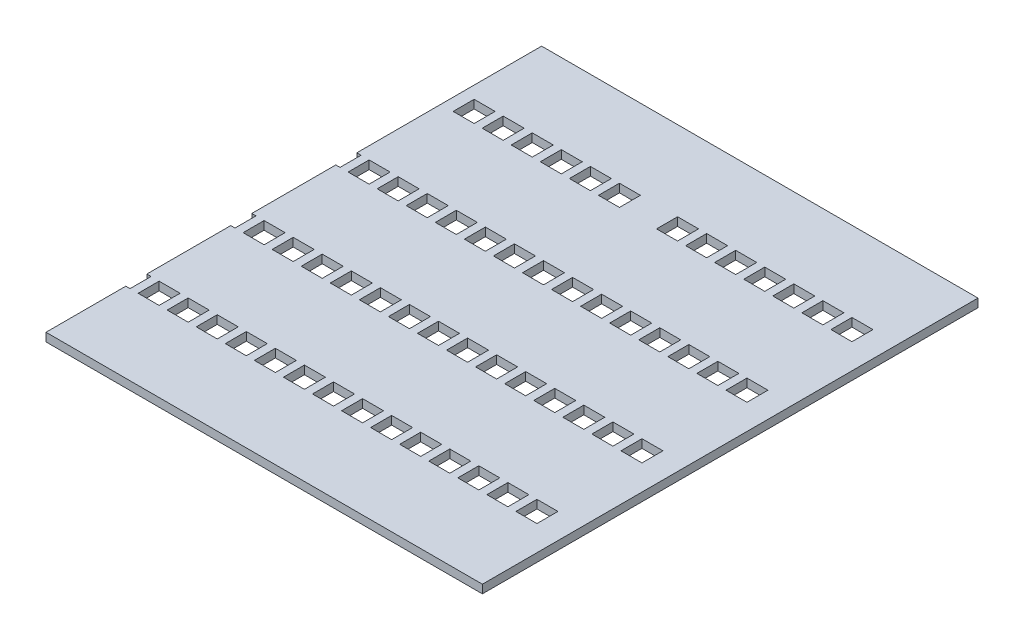
SolidWorks part; units mm, degrees
ref_plane "Front Plane" through (0, 0, 0) normal (0, 0, 1) x (1, 0, 0)
ref_plane "Top Plane" through (0, 0, 0) normal (0, 1, 0) x (1, 0, 0)
ref_plane "Right Plane" through (0, 0, 0) normal (1, 0, 0) x (0, 0, -1)
sketch "Sketch3" plane through (0, 0, 0) normal (0, 1, 0) x (1, 0, 0)
  line L0 (-9.3432, 44.989) -> (-9.3432, 39.989)
  line L1 (-60.7132, 63.989) -> (43.1868, 63.989)
  line L2 (-60.7132, 63.989) -> (-60.7132, -54.011)
  line L3 (-60.7132, -54.011) -> (43.1868, -54.011)
  line L4 (43.1868, 63.989) -> (43.1868, -54.011)
  line L9 (-16.2632, 44.989) -> (-11.2632, 39.989) construction
  line L10 (-16.2632, 39.989) -> (-11.2632, 44.989) construction
  line L11 (-9.3432, 44.989) -> (-4.3432, 44.989)
  line L12 (-4.3432, 44.989) -> (-4.3432, 39.989)
  line L13 (-9.3432, 39.989) -> (-4.3432, 39.989)
  line L14 (-9.3432, 44.989) -> (-4.3432, 39.989) construction
  line L15 (-9.3432, 39.989) -> (-4.3432, 44.989) construction
  line L16 (-2.4232, 44.989) -> (-2.4232, 39.989)
  line L17 (-2.4232, 44.989) -> (2.5768, 44.989)
  line L18 (2.5768, 44.989) -> (2.5768, 39.989)
  line L19 (-2.4232, 39.989) -> (2.5768, 39.989)
  line L20 (-2.4232, 44.989) -> (2.5768, 39.989) construction
  line L21 (-2.4232, 39.989) -> (2.5768, 44.989) construction
  line L22 (4.4968, 44.989) -> (4.4968, 39.989)
  line L23 (4.4968, 44.989) -> (9.4968, 44.989)
  line L24 (9.4968, 44.989) -> (9.4968, 39.989)
  line L25 (4.4968, 39.989) -> (9.4968, 39.989)
  line L26 (4.4968, 44.989) -> (9.4968, 39.989) construction
  line L27 (4.4968, 39.989) -> (9.4968, 44.989) construction
  line L28 (11.4168, 44.989) -> (11.4168, 39.989)
  line L29 (11.4168, 44.989) -> (16.4168, 44.989)
  line L30 (16.4168, 44.989) -> (16.4168, 39.989)
  line L31 (11.4168, 39.989) -> (16.4168, 39.989)
  line L32 (11.4168, 44.989) -> (16.4168, 39.989) construction
  line L33 (11.4168, 39.989) -> (16.4168, 44.989) construction
  line L34 (18.3368, 44.989) -> (18.3368, 39.989)
  line L35 (18.3368, 44.989) -> (23.3368, 44.989)
  line L36 (23.3368, 44.989) -> (23.3368, 39.989)
  line L37 (18.3368, 39.989) -> (23.3368, 39.989)
  line L38 (18.3368, 44.989) -> (23.3368, 39.989) construction
  line L39 (18.3368, 39.989) -> (23.3368, 44.989) construction
  line L40 (25.2568, 44.989) -> (25.2568, 39.989)
  line L41 (25.2568, 44.989) -> (30.2568, 44.989)
  line L42 (30.2568, 44.989) -> (30.2568, 39.989)
  line L43 (25.2568, 39.989) -> (30.2568, 39.989)
  line L46 (32.1768, 44.989) -> (32.1768, 39.989)
  line L47 (32.1768, 44.989) -> (37.1768, 44.989)
  line L48 (37.1768, 44.989) -> (37.1768, 39.989)
  line L49 (32.1768, 39.989) -> (37.1768, 39.989)
  line L52 (-16.2632, 44.989) -> (-9.3432, 44.989) construction
  line L53 (-23.1832, 44.989) -> (-23.1832, 39.989)
  line L54 (-23.1832, 44.989) -> (-18.1832, 44.989)
  line L55 (-18.1832, 44.989) -> (-18.1832, 39.989)
  line L56 (-23.1832, 39.989) -> (-18.1832, 39.989)
  line L57 (-23.1832, 44.989) -> (-18.1832, 39.989) construction
  line L58 (-23.1832, 39.989) -> (-18.1832, 44.989) construction
  line L59 (-30.1032, 44.989) -> (-30.1032, 39.989)
  line L60 (-30.1032, 44.989) -> (-25.1032, 44.989)
  line L61 (-25.1032, 44.989) -> (-25.1032, 39.989)
  line L62 (-30.1032, 39.989) -> (-25.1032, 39.989)
  line L63 (-30.1032, 44.989) -> (-25.1032, 39.989) construction
  line L64 (-30.1032, 39.989) -> (-25.1032, 44.989) construction
  line L65 (-37.0232, 44.989) -> (-37.0232, 39.989)
  line L66 (-37.0232, 44.989) -> (-32.0232, 44.989)
  line L67 (-32.0232, 44.989) -> (-32.0232, 39.989)
  line L68 (-37.0232, 39.989) -> (-32.0232, 39.989)
  line L69 (-37.0232, 44.989) -> (-32.0232, 39.989) construction
  line L70 (-37.0232, 39.989) -> (-32.0232, 44.989) construction
  line L71 (-43.9432, 44.989) -> (-43.9432, 39.989)
  line L72 (-43.9432, 44.989) -> (-38.9432, 44.989)
  line L73 (-38.9432, 44.989) -> (-38.9432, 39.989)
  line L74 (-43.9432, 39.989) -> (-38.9432, 39.989)
  line L75 (-43.9432, 44.989) -> (-38.9432, 39.989) construction
  line L76 (-43.9432, 39.989) -> (-38.9432, 44.989) construction
  line L77 (-50.8632, 44.989) -> (-50.8632, 39.989)
  line L78 (-50.8632, 44.989) -> (-45.8632, 44.989)
  line L79 (-45.8632, 44.989) -> (-45.8632, 39.989)
  line L80 (-50.8632, 39.989) -> (-45.8632, 39.989)
  line L81 (-50.8632, 44.989) -> (-45.8632, 39.989) construction
  line L82 (-50.8632, 39.989) -> (-45.8632, 44.989) construction
  line L96 (-57.7832, 44.989) -> (-57.7832, 39.989)
  line L97 (-57.7832, 39.989) -> (-52.7832, 39.989)
  line L98 (-52.7832, 44.989) -> (-52.7832, 39.989)
  line L99 (-57.7832, 44.989) -> (-52.7832, 44.989)
  line L100 (-57.7832, 39.989) -> (-52.7832, 44.989) construction
  line L101 (-57.7832, 44.989) -> (-52.7832, 39.989) construction
  line L102 (-50.8632, 44.989) -> (-50.8632, 39.989)
  line L103 (-50.8632, 39.989) -> (-45.8632, 39.989)
  line L104 (-45.8632, 44.989) -> (-45.8632, 39.989)
  line L105 (-50.8632, 44.989) -> (-45.8632, 44.989)
  line L106 (-50.8632, 39.989) -> (-45.8632, 44.989) construction
  line L107 (-50.8632, 44.989) -> (-45.8632, 39.989) construction
  line L108 (-43.9432, 44.989) -> (-43.9432, 39.989)
  line L109 (-43.9432, 39.989) -> (-38.9432, 39.989)
  line L110 (-38.9432, 44.989) -> (-38.9432, 39.989)
  line L111 (-43.9432, 44.989) -> (-38.9432, 44.989)
  line L112 (-43.9432, 39.989) -> (-38.9432, 44.989) construction
  line L113 (-43.9432, 44.989) -> (-38.9432, 39.989) construction
  line L114 (-37.0232, 44.989) -> (-37.0232, 39.989)
  line L115 (-37.0232, 39.989) -> (-32.0232, 39.989)
  line L116 (-32.0232, 44.989) -> (-32.0232, 39.989)
  line L117 (-37.0232, 44.989) -> (-32.0232, 44.989)
  line L118 (-37.0232, 39.989) -> (-32.0232, 44.989) construction
  line L119 (-37.0232, 44.989) -> (-32.0232, 39.989) construction
  line L120 (-30.1032, 44.989) -> (-30.1032, 39.989)
  line L121 (-30.1032, 39.989) -> (-25.1032, 39.989)
  line L122 (-25.1032, 44.989) -> (-25.1032, 39.989)
  line L123 (-30.1032, 44.989) -> (-25.1032, 44.989)
  line L124 (-30.1032, 39.989) -> (-25.1032, 44.989) construction
  line L125 (-30.1032, 44.989) -> (-25.1032, 39.989) construction
  line L126 (-23.1832, 44.989) -> (-23.1832, 39.989)
  line L127 (-23.1832, 39.989) -> (-18.1832, 39.989)
  line L128 (-18.1832, 44.989) -> (-18.1832, 39.989)
  line L129 (-23.1832, 44.989) -> (-18.1832, 44.989)
  line L130 (-23.1832, 39.989) -> (-18.1832, 44.989) construction
  line L131 (-23.1832, 44.989) -> (-18.1832, 39.989) construction
  line L136 (-16.2632, 39.989) -> (-11.2632, 44.989) construction
  line L137 (-16.2632, 44.989) -> (-11.2632, 39.989) construction
  line L138 (-9.3432, 44.989) -> (-9.3432, 39.989)
  line L139 (-9.3432, 39.989) -> (-4.3432, 39.989)
  line L140 (-4.3432, 44.989) -> (-4.3432, 39.989)
  line L141 (-9.3432, 44.989) -> (-4.3432, 44.989)
  line L142 (-9.3432, 39.989) -> (-4.3432, 44.989) construction
  line L143 (-9.3432, 44.989) -> (-4.3432, 39.989) construction
  line L144 (-2.4232, 44.989) -> (-2.4232, 39.989)
  line L145 (-2.4232, 39.989) -> (2.5768, 39.989)
  line L146 (2.5768, 44.989) -> (2.5768, 39.989)
  line L147 (-2.4232, 44.989) -> (2.5768, 44.989)
  line L148 (-2.4232, 39.989) -> (2.5768, 44.989) construction
  line L149 (-2.4232, 44.989) -> (2.5768, 39.989) construction
  line L150 (4.4968, 44.989) -> (4.4968, 39.989)
  line L151 (4.4968, 39.989) -> (9.4968, 39.989)
  line L152 (9.4968, 44.989) -> (9.4968, 39.989)
  line L153 (4.4968, 44.989) -> (9.4968, 44.989)
  line L154 (4.4968, 39.989) -> (9.4968, 44.989) construction
  line L155 (4.4968, 44.989) -> (9.4968, 39.989) construction
  line L156 (11.4168, 44.989) -> (11.4168, 39.989)
  line L157 (11.4168, 39.989) -> (16.4168, 39.989)
  line L158 (16.4168, 44.989) -> (16.4168, 39.989)
  line L159 (11.4168, 44.989) -> (16.4168, 44.989)
  line L160 (11.4168, 39.989) -> (16.4168, 44.989) construction
  line L161 (11.4168, 44.989) -> (16.4168, 39.989) construction
  line L162 (18.3368, 44.989) -> (18.3368, 39.989)
  line L163 (18.3368, 39.989) -> (23.3368, 39.989)
  line L164 (23.3368, 44.989) -> (23.3368, 39.989)
  line L165 (18.3368, 44.989) -> (23.3368, 44.989)
  line L166 (18.3368, 39.989) -> (23.3368, 44.989) construction
  line L167 (18.3368, 44.989) -> (23.3368, 39.989) construction
  line L168 (25.2568, 44.989) -> (25.2568, 39.989)
  line L169 (25.2568, 39.989) -> (30.2568, 39.989)
  line L170 (30.2568, 44.989) -> (30.2568, 39.989)
  line L171 (25.2568, 44.989) -> (30.2568, 44.989)
  line L172 (25.2568, 39.989) -> (30.2568, 44.989) construction
  line L173 (25.2568, 44.989) -> (30.2568, 39.989) construction
  line L174 (32.1768, 44.989) -> (32.1768, 39.989)
  line L175 (32.1768, 39.989) -> (37.1768, 39.989)
  line L176 (37.1768, 44.989) -> (37.1768, 39.989)
  line L177 (32.1768, 44.989) -> (37.1768, 44.989)
  line L178 (32.1768, 39.989) -> (37.1768, 44.989) construction
  line L179 (32.1768, 44.989) -> (37.1768, 39.989) construction
  line L180 (-57.7832, 19.989) -> (-57.7832, 14.989)
  line L181 (-57.7832, 14.989) -> (-52.7832, 14.989)
  line L182 (-52.7832, 19.989) -> (-52.7832, 14.989)
  line L183 (-57.7832, 19.989) -> (-52.7832, 19.989)
  line L184 (-57.7832, 14.989) -> (-52.7832, 19.989) construction
  line L185 (-57.7832, 19.989) -> (-52.7832, 14.989) construction
  line L186 (-50.8632, 19.989) -> (-50.8632, 14.989)
  line L187 (-50.8632, 14.989) -> (-45.8632, 14.989)
  line L188 (-45.8632, 19.989) -> (-45.8632, 14.989)
  line L189 (-50.8632, 19.989) -> (-45.8632, 19.989)
  line L190 (-50.8632, 14.989) -> (-45.8632, 19.989) construction
  line L191 (-50.8632, 19.989) -> (-45.8632, 14.989) construction
  line L192 (-43.9432, 19.989) -> (-43.9432, 14.989)
  line L193 (-43.9432, 14.989) -> (-38.9432, 14.989)
  line L194 (-38.9432, 19.989) -> (-38.9432, 14.989)
  line L195 (-43.9432, 19.989) -> (-38.9432, 19.989)
  line L196 (-43.9432, 14.989) -> (-38.9432, 19.989) construction
  line L197 (-43.9432, 19.989) -> (-38.9432, 14.989) construction
  line L198 (-37.0232, 19.989) -> (-37.0232, 14.989)
  line L199 (-37.0232, 14.989) -> (-32.0232, 14.989)
  line L200 (-32.0232, 19.989) -> (-32.0232, 14.989)
  line L201 (-37.0232, 19.989) -> (-32.0232, 19.989)
  line L202 (-37.0232, 14.989) -> (-32.0232, 19.989) construction
  line L203 (-37.0232, 19.989) -> (-32.0232, 14.989) construction
  line L204 (-30.1032, 19.989) -> (-30.1032, 14.989)
  line L205 (-30.1032, 14.989) -> (-25.1032, 14.989)
  line L206 (-25.1032, 19.989) -> (-25.1032, 14.989)
  line L207 (-30.1032, 19.989) -> (-25.1032, 19.989)
  line L208 (-30.1032, 14.989) -> (-25.1032, 19.989) construction
  line L209 (-30.1032, 19.989) -> (-25.1032, 14.989) construction
  line L210 (-23.1832, 19.989) -> (-23.1832, 14.989)
  line L211 (-23.1832, 14.989) -> (-18.1832, 14.989)
  line L212 (-18.1832, 19.989) -> (-18.1832, 14.989)
  line L213 (-23.1832, 19.989) -> (-18.1832, 19.989)
  line L214 (-23.1832, 14.989) -> (-18.1832, 19.989) construction
  line L215 (-23.1832, 19.989) -> (-18.1832, 14.989) construction
  line L216 (-16.2632, 19.989) -> (-16.2632, 14.989)
  line L217 (-16.2632, 14.989) -> (-11.2632, 14.989)
  line L218 (-11.2632, 19.989) -> (-11.2632, 14.989)
  line L219 (-16.2632, 19.989) -> (-11.2632, 19.989)
  line L220 (-16.2632, 14.989) -> (-11.2632, 19.989) construction
  line L221 (-16.2632, 19.989) -> (-11.2632, 14.989) construction
  line L222 (-9.3432, 19.989) -> (-9.3432, 14.989)
  line L223 (-9.3432, 14.989) -> (-4.3432, 14.989)
  line L224 (-4.3432, 19.989) -> (-4.3432, 14.989)
  line L225 (-9.3432, 19.989) -> (-4.3432, 19.989)
  line L226 (-9.3432, 14.989) -> (-4.3432, 19.989) construction
  line L227 (-9.3432, 19.989) -> (-4.3432, 14.989) construction
  line L228 (-2.4232, 19.989) -> (-2.4232, 14.989)
  line L229 (-2.4232, 14.989) -> (2.5768, 14.989)
  line L230 (2.5768, 19.989) -> (2.5768, 14.989)
  line L231 (-2.4232, 19.989) -> (2.5768, 19.989)
  line L232 (-2.4232, 14.989) -> (2.5768, 19.989) construction
  line L233 (-2.4232, 19.989) -> (2.5768, 14.989) construction
  line L234 (4.4968, 19.989) -> (4.4968, 14.989)
  line L235 (4.4968, 14.989) -> (9.4968, 14.989)
  line L236 (9.4968, 19.989) -> (9.4968, 14.989)
  line L237 (4.4968, 19.989) -> (9.4968, 19.989)
  line L238 (4.4968, 14.989) -> (9.4968, 19.989) construction
  line L239 (4.4968, 19.989) -> (9.4968, 14.989) construction
  line L240 (11.4168, 19.989) -> (11.4168, 14.989)
  line L241 (11.4168, 14.989) -> (16.4168, 14.989)
  line L242 (16.4168, 19.989) -> (16.4168, 14.989)
  line L243 (11.4168, 19.989) -> (16.4168, 19.989)
  line L244 (11.4168, 14.989) -> (16.4168, 19.989) construction
  line L245 (11.4168, 19.989) -> (16.4168, 14.989) construction
  line L246 (18.3368, 19.989) -> (18.3368, 14.989)
  line L247 (18.3368, 14.989) -> (23.3368, 14.989)
  line L248 (23.3368, 19.989) -> (23.3368, 14.989)
  line L249 (18.3368, 19.989) -> (23.3368, 19.989)
  line L250 (18.3368, 14.989) -> (23.3368, 19.989) construction
  line L251 (18.3368, 19.989) -> (23.3368, 14.989) construction
  line L252 (25.2568, 19.989) -> (25.2568, 14.989)
  line L253 (25.2568, 14.989) -> (30.2568, 14.989)
  line L254 (30.2568, 19.989) -> (30.2568, 14.989)
  line L255 (25.2568, 19.989) -> (30.2568, 19.989)
  line L256 (25.2568, 14.989) -> (30.2568, 19.989) construction
  line L257 (25.2568, 19.989) -> (30.2568, 14.989) construction
  line L258 (32.1768, 19.989) -> (32.1768, 14.989)
  line L259 (32.1768, 14.989) -> (37.1768, 14.989)
  line L260 (37.1768, 19.989) -> (37.1768, 14.989)
  line L261 (32.1768, 19.989) -> (37.1768, 19.989)
  line L262 (32.1768, 14.989) -> (37.1768, 19.989) construction
  line L263 (32.1768, 19.989) -> (37.1768, 14.989) construction
  line L264 (-57.7832, -5.011) -> (-57.7832, -10.011)
  line L265 (-57.7832, -10.011) -> (-52.7832, -10.011)
  line L266 (-52.7832, -5.011) -> (-52.7832, -10.011)
  line L267 (-57.7832, -5.011) -> (-52.7832, -5.011)
  line L268 (-57.7832, -10.011) -> (-52.7832, -5.011) construction
  line L269 (-57.7832, -5.011) -> (-52.7832, -10.011) construction
  line L270 (-50.8632, -5.011) -> (-50.8632, -10.011)
  line L271 (-50.8632, -10.011) -> (-45.8632, -10.011)
  line L272 (-45.8632, -5.011) -> (-45.8632, -10.011)
  line L273 (-50.8632, -5.011) -> (-45.8632, -5.011)
  line L274 (-50.8632, -10.011) -> (-45.8632, -5.011) construction
  line L275 (-50.8632, -5.011) -> (-45.8632, -10.011) construction
  line L276 (-43.9432, -5.011) -> (-43.9432, -10.011)
  line L277 (-43.9432, -10.011) -> (-38.9432, -10.011)
  line L278 (-38.9432, -5.011) -> (-38.9432, -10.011)
  line L279 (-43.9432, -5.011) -> (-38.9432, -5.011)
  line L280 (-43.9432, -10.011) -> (-38.9432, -5.011) construction
  line L281 (-43.9432, -5.011) -> (-38.9432, -10.011) construction
  line L282 (-37.0232, -5.011) -> (-37.0232, -10.011)
  line L283 (-37.0232, -10.011) -> (-32.0232, -10.011)
  line L284 (-32.0232, -5.011) -> (-32.0232, -10.011)
  line L285 (-37.0232, -5.011) -> (-32.0232, -5.011)
  line L286 (-37.0232, -10.011) -> (-32.0232, -5.011) construction
  line L287 (-37.0232, -5.011) -> (-32.0232, -10.011) construction
  line L288 (-30.1032, -5.011) -> (-30.1032, -10.011)
  line L289 (-30.1032, -10.011) -> (-25.1032, -10.011)
  line L290 (-25.1032, -5.011) -> (-25.1032, -10.011)
  line L291 (-30.1032, -5.011) -> (-25.1032, -5.011)
  line L292 (-30.1032, -10.011) -> (-25.1032, -5.011) construction
  line L293 (-30.1032, -5.011) -> (-25.1032, -10.011) construction
  line L294 (-23.1832, -5.011) -> (-23.1832, -10.011)
  line L295 (-23.1832, -10.011) -> (-18.1832, -10.011)
  line L296 (-18.1832, -5.011) -> (-18.1832, -10.011)
  line L297 (-23.1832, -5.011) -> (-18.1832, -5.011)
  line L298 (-23.1832, -10.011) -> (-18.1832, -5.011) construction
  line L299 (-23.1832, -5.011) -> (-18.1832, -10.011) construction
  line L300 (-16.2632, -5.011) -> (-16.2632, -10.011)
  line L301 (-16.2632, -10.011) -> (-11.2632, -10.011)
  line L302 (-11.2632, -5.011) -> (-11.2632, -10.011)
  line L303 (-16.2632, -5.011) -> (-11.2632, -5.011)
  line L304 (-16.2632, -10.011) -> (-11.2632, -5.011) construction
  line L305 (-16.2632, -5.011) -> (-11.2632, -10.011) construction
  line L306 (-9.3432, -5.011) -> (-9.3432, -10.011)
  line L307 (-9.3432, -10.011) -> (-4.3432, -10.011)
  line L308 (-4.3432, -5.011) -> (-4.3432, -10.011)
  line L309 (-9.3432, -5.011) -> (-4.3432, -5.011)
  line L310 (-9.3432, -10.011) -> (-4.3432, -5.011) construction
  line L311 (-9.3432, -5.011) -> (-4.3432, -10.011) construction
  line L312 (-2.4232, -5.011) -> (-2.4232, -10.011)
  line L313 (-2.4232, -10.011) -> (2.5768, -10.011)
  line L314 (2.5768, -5.011) -> (2.5768, -10.011)
  line L315 (-2.4232, -5.011) -> (2.5768, -5.011)
  line L316 (-2.4232, -10.011) -> (2.5768, -5.011) construction
  line L317 (-2.4232, -5.011) -> (2.5768, -10.011) construction
  line L318 (4.4968, -5.011) -> (4.4968, -10.011)
  line L319 (4.4968, -10.011) -> (9.4968, -10.011)
  line L320 (9.4968, -5.011) -> (9.4968, -10.011)
  line L321 (4.4968, -5.011) -> (9.4968, -5.011)
  line L322 (4.4968, -10.011) -> (9.4968, -5.011) construction
  line L323 (4.4968, -5.011) -> (9.4968, -10.011) construction
  line L324 (11.4168, -5.011) -> (11.4168, -10.011)
  line L325 (11.4168, -10.011) -> (16.4168, -10.011)
  line L326 (16.4168, -5.011) -> (16.4168, -10.011)
  line L327 (11.4168, -5.011) -> (16.4168, -5.011)
  line L328 (11.4168, -10.011) -> (16.4168, -5.011) construction
  line L329 (11.4168, -5.011) -> (16.4168, -10.011) construction
  line L330 (18.3368, -5.011) -> (18.3368, -10.011)
  line L331 (18.3368, -10.011) -> (23.3368, -10.011)
  line L332 (23.3368, -5.011) -> (23.3368, -10.011)
  line L333 (18.3368, -5.011) -> (23.3368, -5.011)
  line L334 (18.3368, -10.011) -> (23.3368, -5.011) construction
  line L335 (18.3368, -5.011) -> (23.3368, -10.011) construction
  line L336 (25.2568, -5.011) -> (25.2568, -10.011)
  line L337 (25.2568, -10.011) -> (30.2568, -10.011)
  line L338 (30.2568, -5.011) -> (30.2568, -10.011)
  line L339 (25.2568, -5.011) -> (30.2568, -5.011)
  line L340 (25.2568, -10.011) -> (30.2568, -5.011) construction
  line L341 (25.2568, -5.011) -> (30.2568, -10.011) construction
  line L342 (32.1768, -5.011) -> (32.1768, -10.011)
  line L343 (32.1768, -10.011) -> (37.1768, -10.011)
  line L344 (37.1768, -5.011) -> (37.1768, -10.011)
  line L345 (32.1768, -5.011) -> (37.1768, -5.011)
  line L346 (32.1768, -10.011) -> (37.1768, -5.011) construction
  line L347 (32.1768, -5.011) -> (37.1768, -10.011) construction
  line L348 (-57.7832, -30.011) -> (-57.7832, -35.011)
  line L349 (-57.7832, -35.011) -> (-52.7832, -35.011)
  line L350 (-52.7832, -30.011) -> (-52.7832, -35.011)
  line L351 (-57.7832, -30.011) -> (-52.7832, -30.011)
  line L352 (-57.7832, -35.011) -> (-52.7832, -30.011) construction
  line L353 (-57.7832, -30.011) -> (-52.7832, -35.011) construction
  line L354 (-50.8632, -30.011) -> (-50.8632, -35.011)
  line L355 (-50.8632, -35.011) -> (-45.8632, -35.011)
  line L356 (-45.8632, -30.011) -> (-45.8632, -35.011)
  line L357 (-50.8632, -30.011) -> (-45.8632, -30.011)
  line L358 (-50.8632, -35.011) -> (-45.8632, -30.011) construction
  line L359 (-50.8632, -30.011) -> (-45.8632, -35.011) construction
  line L360 (-43.9432, -30.011) -> (-43.9432, -35.011)
  line L361 (-43.9432, -35.011) -> (-38.9432, -35.011)
  line L362 (-38.9432, -30.011) -> (-38.9432, -35.011)
  line L363 (-43.9432, -30.011) -> (-38.9432, -30.011)
  line L364 (-43.9432, -35.011) -> (-38.9432, -30.011) construction
  line L365 (-43.9432, -30.011) -> (-38.9432, -35.011) construction
  line L366 (-37.0232, -30.011) -> (-37.0232, -35.011)
  line L367 (-37.0232, -35.011) -> (-32.0232, -35.011)
  line L368 (-32.0232, -30.011) -> (-32.0232, -35.011)
  line L369 (-37.0232, -30.011) -> (-32.0232, -30.011)
  line L370 (-37.0232, -35.011) -> (-32.0232, -30.011) construction
  line L371 (-37.0232, -30.011) -> (-32.0232, -35.011) construction
  line L372 (-30.1032, -30.011) -> (-30.1032, -35.011)
  line L373 (-30.1032, -35.011) -> (-25.1032, -35.011)
  line L374 (-25.1032, -30.011) -> (-25.1032, -35.011)
  line L375 (-30.1032, -30.011) -> (-25.1032, -30.011)
  line L376 (-30.1032, -35.011) -> (-25.1032, -30.011) construction
  line L377 (-30.1032, -30.011) -> (-25.1032, -35.011) construction
  line L378 (-23.1832, -30.011) -> (-23.1832, -35.011)
  line L379 (-23.1832, -35.011) -> (-18.1832, -35.011)
  line L380 (-18.1832, -30.011) -> (-18.1832, -35.011)
  line L381 (-23.1832, -30.011) -> (-18.1832, -30.011)
  line L382 (-23.1832, -35.011) -> (-18.1832, -30.011) construction
  line L383 (-23.1832, -30.011) -> (-18.1832, -35.011) construction
  line L384 (-16.2632, -30.011) -> (-16.2632, -35.011)
  line L385 (-16.2632, -35.011) -> (-11.2632, -35.011)
  line L386 (-11.2632, -30.011) -> (-11.2632, -35.011)
  line L387 (-16.2632, -30.011) -> (-11.2632, -30.011)
  line L388 (-16.2632, -35.011) -> (-11.2632, -30.011) construction
  line L389 (-16.2632, -30.011) -> (-11.2632, -35.011) construction
  line L390 (-9.3432, -30.011) -> (-9.3432, -35.011)
  line L391 (-9.3432, -35.011) -> (-4.3432, -35.011)
  line L392 (-4.3432, -30.011) -> (-4.3432, -35.011)
  line L393 (-9.3432, -30.011) -> (-4.3432, -30.011)
  line L394 (-9.3432, -35.011) -> (-4.3432, -30.011) construction
  line L395 (-9.3432, -30.011) -> (-4.3432, -35.011) construction
  line L396 (-2.4232, -30.011) -> (-2.4232, -35.011)
  line L397 (-2.4232, -35.011) -> (2.5768, -35.011)
  line L398 (2.5768, -30.011) -> (2.5768, -35.011)
  line L399 (-2.4232, -30.011) -> (2.5768, -30.011)
  line L400 (-2.4232, -35.011) -> (2.5768, -30.011) construction
  line L401 (-2.4232, -30.011) -> (2.5768, -35.011) construction
  line L402 (4.4968, -30.011) -> (4.4968, -35.011)
  line L403 (4.4968, -35.011) -> (9.4968, -35.011)
  line L404 (9.4968, -30.011) -> (9.4968, -35.011)
  line L405 (4.4968, -30.011) -> (9.4968, -30.011)
  line L406 (4.4968, -35.011) -> (9.4968, -30.011) construction
  line L407 (4.4968, -30.011) -> (9.4968, -35.011) construction
  line L408 (11.4168, -30.011) -> (11.4168, -35.011)
  line L409 (11.4168, -35.011) -> (16.4168, -35.011)
  line L410 (16.4168, -30.011) -> (16.4168, -35.011)
  line L411 (11.4168, -30.011) -> (16.4168, -30.011)
  line L412 (11.4168, -35.011) -> (16.4168, -30.011) construction
  line L413 (11.4168, -30.011) -> (16.4168, -35.011) construction
  line L414 (18.3368, -30.011) -> (18.3368, -35.011)
  line L415 (18.3368, -35.011) -> (23.3368, -35.011)
  line L416 (23.3368, -30.011) -> (23.3368, -35.011)
  line L417 (18.3368, -30.011) -> (23.3368, -30.011)
  line L418 (18.3368, -35.011) -> (23.3368, -30.011) construction
  line L419 (18.3368, -30.011) -> (23.3368, -35.011) construction
  line L420 (25.2568, -30.011) -> (25.2568, -35.011)
  line L421 (25.2568, -35.011) -> (30.2568, -35.011)
  line L422 (30.2568, -30.011) -> (30.2568, -35.011)
  line L423 (25.2568, -30.011) -> (30.2568, -30.011)
  line L424 (25.2568, -35.011) -> (30.2568, -30.011) construction
  line L425 (25.2568, -30.011) -> (30.2568, -35.011) construction
  line L426 (32.1768, -30.011) -> (32.1768, -35.011)
  line L427 (32.1768, -35.011) -> (37.1768, -35.011)
  line L428 (37.1768, -30.011) -> (37.1768, -35.011)
  line L429 (32.1768, -30.011) -> (37.1768, -30.011)
  line L430 (32.1768, -35.011) -> (37.1768, -30.011) construction
  line L431 (32.1768, -30.011) -> (37.1768, -35.011) construction
  line L432 (-64.7032, 19.989) -> (-64.7032, 14.989)
  line L433 (-64.7032, 14.989) -> (-59.7032, 14.989)
  line L434 (-59.7032, 19.989) -> (-59.7032, 14.989)
  line L435 (-64.7032, 19.989) -> (-59.7032, 19.989)
  line L436 (-64.7032, 14.989) -> (-59.7032, 19.989) construction
  line L437 (-64.7032, 19.989) -> (-59.7032, 14.989) construction
  line L438 (-64.7032, -5.011) -> (-64.7032, -10.011)
  line L439 (-64.7032, -10.011) -> (-59.7032, -10.011)
  line L440 (-59.7032, -5.011) -> (-59.7032, -10.011)
  line L441 (-64.7032, -5.011) -> (-59.7032, -5.011)
  line L442 (-64.7032, -10.011) -> (-59.7032, -5.011) construction
  line L443 (-64.7032, -5.011) -> (-59.7032, -10.011) construction
  line L444 (-64.7032, -30.011) -> (-64.7032, -35.011)
  line L445 (-64.7032, -35.011) -> (-59.7032, -35.011)
  line L446 (-59.7032, -30.011) -> (-59.7032, -35.011)
  line L447 (-64.7032, -30.011) -> (-59.7032, -30.011)
  line L448 (-64.7032, -35.011) -> (-59.7032, -30.011) construction
  line L449 (-64.7032, -30.011) -> (-59.7032, -35.011) construction
  line L450 (-64.7032, 44.989) -> (-57.7832, 44.989) construction
  point P4 (-13.7632, 29.989)
  point P5 (-13.7632, 42.489)
  point P6 (-13.7632, 4.989)
  point P11 (-13.7632, 42.489)
  point P12 (-13.7632, 17.489)
  point P13 (0, 0)
  point P16 (-13.7632, 42.489)
  point P45 (0, 0)
  dimension "D5" = 6
  dimension "D11" = 15
  dimension "D9" = 4
extrude "Boss-Extrude1" add sketch "Sketch3" along normal blind 2
